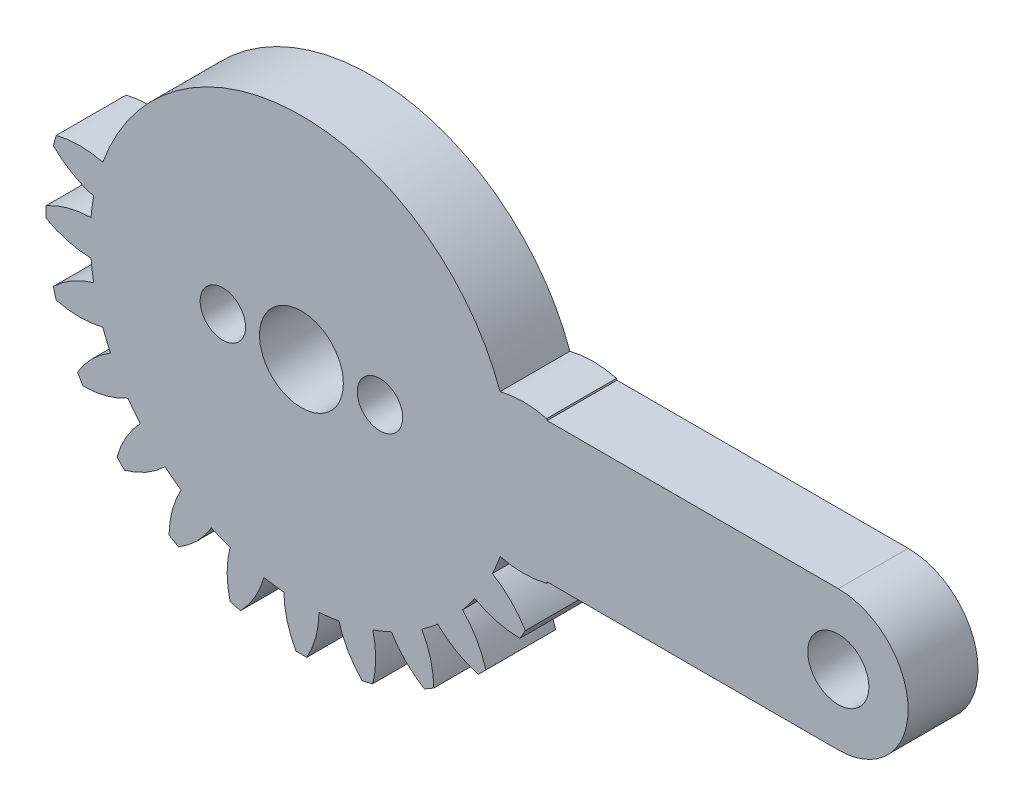
SolidWorks part; units mm, degrees
ref_plane "Front Plane" through (0, 0, 0) normal (0, 0, 1) x (1, 0, 0)
ref_plane "Top Plane" through (0, 0, 0) normal (0, 1, 0) x (1, 0, 0)
ref_plane "Right Plane" through (0, 0, 0) normal (1, 0, 0) x (0, 0, -1)
sketch "Sketch1" plane through (0, 0, 0) normal (0, 0, 1) x (1, 0, 0)
  line L0 (0, 0) -> (0, 14.63) construction
  line L1 (0, 0) -> (32.007, 0) construction
  line L2 (11.4091, 4) -> (30.75, 4)
  line L3 (11.4091, -4) -> (30.75, -4)
  circle A0 centre (0, 0) radius 12.09
  circle A1 centre (0, 0) radius 14.63
  circle A2 centre (0, 0) radius 1.75
  arc A3 (0.31, 14.6267) -> (1.0062, 12.0481) centre (-4.3933, 11.9736) cw
  arc A4 (-0.31, 14.6267) -> (-1.0062, 12.0481) centre (4.3933, 11.9736) ccw
  arc A5 (3.4862, 14.2086) -> (2.1464, 11.898) centre (7.3426, 10.4285) ccw
  arc A6 (4.0851, 14.0481) -> (4.0902, 11.3771) centre (-1.1446, 12.7027) cw
  arc A7 (7.0449, 12.8221) -> (5.1526, 10.937) centre (9.7915, 8.1728) ccw
  arc A8 (7.5818, 12.5121) -> (6.8954, 9.9308) centre (2.1821, 12.5661) cw
  arc A9 (10.1234, 10.5619) -> (7.8078, 9.2308) centre (11.5731, 5.3601) ccw
  arc A10 (10.5619, 10.1234) -> (9.2308, 7.8078) centre (5.3601, 11.5731) cw
  arc A11 (12.5121, 7.5818) -> (9.9308, 6.8954) centre (12.5661, 2.1821) ccw
  arc A12 (12.8221, 7.0449) -> (10.937, 5.1526) centre (8.1728, 9.7915) cw
  arc A13 (14.0481, 4.0851) -> (11.3771, 4.0902) centre (12.7027, -1.1446) ccw
  arc A14 (14.2086, 3.4862) -> (11.898, 2.1464) centre (10.4285, 7.3426) cw
  arc A15 (14.6267, 0.31) -> (12.0481, 1.0062) centre (11.9736, -4.3933) ccw
  arc A16 (14.6267, -0.31) -> (12.0481, -1.0062) centre (11.9736, 4.3933) cw
  arc A17 (14.2086, -3.4862) -> (11.898, -2.1464) centre (10.4285, -7.3426) ccw
  arc A18 (14.0481, -4.0851) -> (11.3771, -4.0902) centre (12.7027, 1.1446) cw
  arc A19 (12.8221, -7.0449) -> (10.937, -5.1526) centre (8.1728, -9.7915) ccw
  arc A20 (12.5121, -7.5818) -> (9.9308, -6.8954) centre (12.5661, -2.1821) cw
  arc A21 (10.5619, -10.1234) -> (9.2308, -7.8078) centre (5.3601, -11.5731) ccw
  arc A22 (10.1234, -10.5619) -> (7.8078, -9.2308) centre (11.5731, -5.3601) cw
  arc A23 (7.5818, -12.5121) -> (6.8954, -9.9308) centre (2.1821, -12.5661) ccw
  arc A24 (7.0449, -12.8221) -> (5.1526, -10.937) centre (9.7915, -8.1728) cw
  arc A25 (4.0851, -14.0481) -> (4.0902, -11.3771) centre (-1.1446, -12.7027) ccw
  arc A26 (3.4862, -14.2086) -> (2.1464, -11.898) centre (7.3426, -10.4285) cw
  arc A27 (0.31, -14.6267) -> (1.0062, -12.0481) centre (-4.3933, -11.9736) ccw
  arc A28 (-0.31, -14.6267) -> (-1.0062, -12.0481) centre (4.3933, -11.9736) cw
  arc A29 (-3.4862, -14.2086) -> (-2.1464, -11.898) centre (-7.3426, -10.4285) ccw
  arc A30 (-4.0851, -14.0481) -> (-4.0902, -11.3771) centre (1.1446, -12.7027) cw
  arc A31 (-7.0449, -12.8221) -> (-5.1526, -10.937) centre (-9.7915, -8.1728) ccw
  arc A32 (-7.5818, -12.5121) -> (-6.8954, -9.9308) centre (-2.1821, -12.5661) cw
  arc A33 (-10.1234, -10.5619) -> (-7.8078, -9.2308) centre (-11.5731, -5.3601) ccw
  arc A34 (-10.5619, -10.1234) -> (-9.2308, -7.8078) centre (-5.3601, -11.5731) cw
  arc A35 (-12.5121, -7.5818) -> (-9.9308, -6.8954) centre (-12.5661, -2.1821) ccw
  arc A36 (-12.8221, -7.0449) -> (-10.937, -5.1526) centre (-8.1728, -9.7915) cw
  arc A37 (-14.0481, -4.0851) -> (-11.3771, -4.0902) centre (-12.7027, 1.1446) ccw
  arc A38 (-14.2086, -3.4862) -> (-11.898, -2.1464) centre (-10.4285, -7.3426) cw
  arc A39 (-14.6267, -0.31) -> (-12.0481, -1.0062) centre (-11.9736, 4.3933) ccw
  arc A40 (-14.6267, 0.31) -> (-12.0481, 1.0062) centre (-11.9736, -4.3933) cw
  arc A41 (-14.2086, 3.4862) -> (-11.898, 2.1464) centre (-10.4285, 7.3426) ccw
  arc A42 (-14.0481, 4.0851) -> (-11.3771, 4.0902) centre (-12.7027, -1.1446) cw
  arc A43 (-12.8221, 7.0449) -> (-10.937, 5.1526) centre (-8.1728, 9.7915) ccw
  arc A44 (-12.5121, 7.5818) -> (-9.9308, 6.8954) centre (-12.5661, 2.1821) cw
  arc A45 (-10.5619, 10.1234) -> (-9.2308, 7.8078) centre (-5.3601, 11.5731) ccw
  arc A46 (-10.1234, 10.5619) -> (-7.8078, 9.2308) centre (-11.5731, 5.3601) cw
  arc A47 (-7.5818, 12.5121) -> (-6.8954, 9.9308) centre (-2.1821, 12.5661) ccw
  arc A48 (-7.0449, 12.8221) -> (-5.1526, 10.937) centre (-9.7915, 8.1728) cw
  arc A49 (-4.0851, 14.0481) -> (-4.0902, 11.3771) centre (1.1446, 12.7027) ccw
  arc A50 (-3.4862, 14.2086) -> (-2.1464, 11.898) centre (-7.3426, 10.4285) cw
  arc A51 (30.75, 4) -> (30.75, -4) centre (30.75, 0) cw
  circle A52 centre (30.75, 0) radius 1.75
  point P2 (-30.2306, -0.1946)
  point P156 (-0.3594, -0.3009)
  point P157 (0, 0)
  point P158 (13.8364, -4.7531)
  point P159 (14.0249, -4.1348)
  point P161 (-53.8753, -8.6052)
  point P163 (14.0249, -4.1348)
  point P164 (0, 0)
  point P165 (-31.6903, 0.6414)
  dimension "D1" = 3.5
  dimension "D2" = 24.18
  dimension "D3" = 29.26
  dimension "D6" = 5.4
  dimension "D7" = 24
  dimension "D8" = 30.75
  dimension "D9" = 4
  dimension "D10" = 3.5
  dimension "D4" = 0.62
  dimension "D11" = 1.15
extrude "Boss-Extrude1" add sketch "Sketch1" along normal blind 4 contours A0 | A51 L2 A1 L3 A52 | A18 A1 L3 A0 | A16 A1 A15 A0 | A15 A1 A14 A0 | A14 A1 L2 A0 | A1 A13 A0 L2 | A1 A17 A0 L3 | A17 A1 A16 A0 | A20 A1 A19 A0 | A22 A1 A21 A0 | A24 A1 A23 A0 | A26 A1 A25 A0 | A28 A1 A27 A0 | A30 A1 A29 A0 | A32 A1 A31 A0 | A34 A1 A33 A0 | A36 A1 A35 A0 | A38 A1 A37 A0 | A40 A1 A39 A0 | A42 A1 A41 A0
sketch "Sketch6" plane through (0, 0, 4) normal (0, 0, 1) x (1, 0, 0)
  line L0 (4.5, 0) -> (-4.5, 0) construction
  circle A0 centre (4.5, 0) radius 1.3
  circle A1 centre (-4.5, 0) radius 1.3
  circle A3 centre (0, 0) radius 1.75 construction
  circle A4 centre (0, 0) radius 2.4
  point P6 (0, 0)
  dimension "D1" = 4.5
  dimension "D2" = 9
  dimension "D3" = 2.6
  dimension "D4" = 4.8
extrude "Cut-Extrude1" cut sketch "Sketch6" against normal through all
